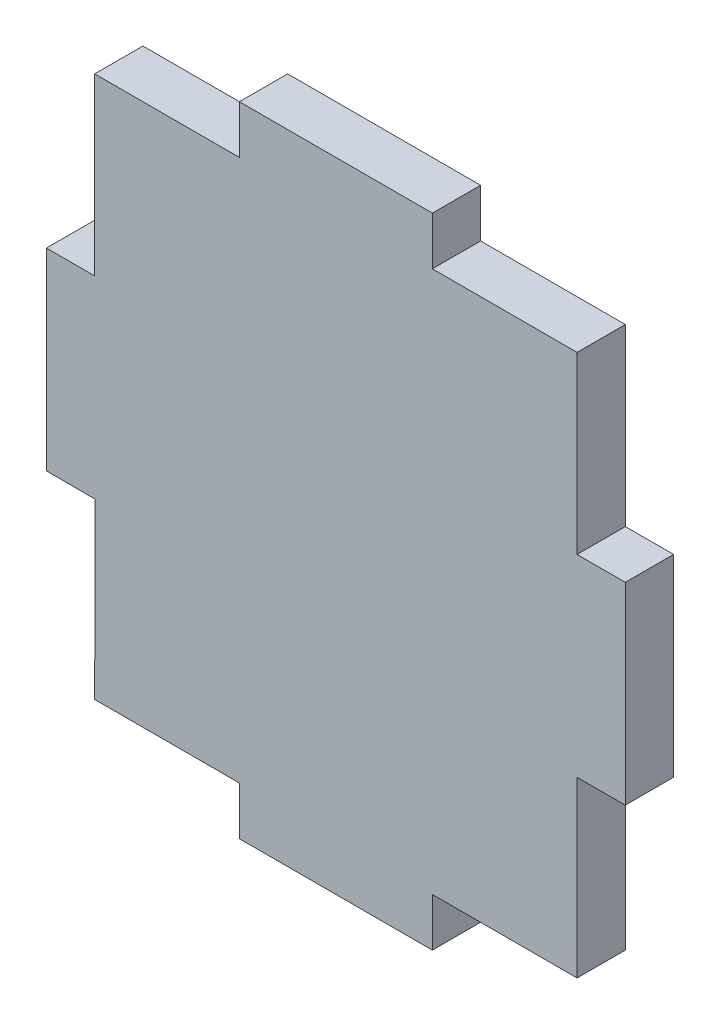
SolidWorks part; units mm, degrees
material "Plain Carbon Steel"
ref_plane "Front Plane" through (0, 0, 0) normal (0, 0, 1) x (1, 0, 0)
ref_plane "Top Plane" through (0, 0, 0) normal (0, 1, 0) x (1, 0, 0)
ref_plane "Right Plane" through (0, 0, 0) normal (1, 0, 0) x (0, 0, -1)
sketch "Model" plane through (0, 0, 0) normal (0, 0, 1) x (1, 0, 0)
  line L0 (823.747, -110.7111) -> (823.747, -92.5742)
  line L1 (838.7355, -148.7291) -> (823.747, -148.7291)
  line L2 (858.747, -148.7291) -> (873.747, -148.7291)
  line L3 (878.747, -130.7111) -> (873.747, -130.7225)
  line L4 (823.747, -92.5742) -> (838.7355, -92.5742)
  line L5 (873.747, -148.7291) -> (873.747, -130.7225)
  line L6 (873.747, -110.7111) -> (878.747, -110.7111)
  line L7 (838.747, -153.7291) -> (858.747, -153.7291)
  line L8 (818.747, -110.7111) -> (823.747, -110.7111)
  line L9 (838.7355, -148.7291) -> (838.747, -153.7291)
  line L10 (838.747, -87.5742) -> (858.747, -87.5742)
  line L11 (838.7355, -92.5742) -> (838.747, -87.5742)
  line L12 (823.7888, -130.7227) -> (818.747, -130.7111)
  line L13 (858.747, -87.5742) -> (858.747, -92.5742)
  line L14 (873.747, -92.5742) -> (873.747, -110.7111)
  line L15 (878.747, -110.7111) -> (878.747, -130.7111)
  line L16 (858.747, -92.5742) -> (873.747, -92.5742)
  line L17 (818.747, -130.7111) -> (818.747, -110.7111)
  line L18 (823.747, -148.7291) -> (823.7888, -130.7227)
  line L19 (858.747, -153.7291) -> (858.747, -148.7291)
  line L20 (841.5508, -121.7141) -> (841.0107, -121.7141)
  line L21 (841.0107, -121.7141) -> (842.0816, -121.7141)
  line L22 (842.0816, -121.7141) -> (841.5508, -121.7141)
  line L23 (841.5508, -121.7141) -> (841.5508, -123.8681)
  line L24 (841.5508, -123.8681) -> (841.5508, -121.7141)
  line L25 (842.5092, -123.8681) -> (842.5092, -121.7141)
  line L26 (842.5092, -121.7141) -> (842.5092, -122.7756)
  line L27 (842.5092, -122.7756) -> (843.6269, -122.7756)
  line L28 (843.6269, -122.7756) -> (843.6269, -121.7141)
  line L29 (843.6269, -121.7141) -> (843.6269, -123.8681)
  line L30 (843.6269, -123.8681) -> (843.6269, -122.7754)
  line L31 (843.6269, -122.7754) -> (842.5092, -122.7754)
  line L32 (842.5092, -122.7754) -> (842.5092, -123.8681)
  line L33 (844.0077, -121.7111) -> (844.0077, -123.8681)
  line L34 (844.5077, -123.4747) -> (844.5077, -123.6277)
  line L35 (844.5077, -123.6277) -> (844.5177, -123.6758)
  line L36 (844.5177, -123.6758) -> (844.5479, -123.7202)
  line L37 (844.5479, -123.7202) -> (844.6685, -123.7978)
  line L38 (844.6685, -123.7978) -> (844.8492, -123.8505)
  line L39 (844.8492, -123.8505) -> (845.0696, -123.8681)
  line L40 (845.0696, -123.8681) -> (845.2901, -123.8505)
  line L41 (845.2901, -123.8505) -> (845.4708, -123.7978)
  line L42 (845.4708, -123.7978) -> (845.5914, -123.7202)
  line L43 (845.5914, -123.7202) -> (845.6216, -123.6758)
  line L44 (845.6216, -123.6758) -> (845.6316, -123.6277)
  line L45 (845.6316, -123.6277) -> (845.6378, -122.9909)
  line L46 (845.6378, -122.9909) -> (845.6096, -122.865)
  line L47 (845.6096, -122.865) -> (845.5282, -122.7747)
  line L48 (845.5282, -122.7747) -> (845.3935, -122.7199)
  line L49 (845.3935, -122.7199) -> (845.2054, -122.7005)
  line L50 (845.2054, -122.7005) -> (844.8648, -122.692)
  line L51 (844.8648, -122.692) -> (844.7012, -122.6725)
  line L52 (844.7012, -122.6725) -> (844.5561, -122.5905)
  line L53 (844.5561, -122.5905) -> (844.5198, -122.5419)
  line L54 (844.5198, -122.5419) -> (844.5077, -122.4883)
  line L55 (844.5077, -122.4883) -> (844.5077, -121.9545)
  line L56 (844.5077, -121.9545) -> (844.5177, -121.9064)
  line L57 (844.5177, -121.9064) -> (844.5479, -121.862)
  line L58 (844.5479, -121.862) -> (844.6685, -121.7843)
  line L59 (844.6685, -121.7843) -> (844.8492, -121.7317)
  line L60 (844.8492, -121.7317) -> (845.0696, -121.7141)
  line L61 (845.0696, -121.7141) -> (845.2901, -121.7317)
  line L62 (845.2901, -121.7317) -> (845.4708, -121.7843)
  line L63 (845.4708, -121.7843) -> (845.5914, -121.862)
  line L64 (845.5914, -121.862) -> (845.6216, -121.9064)
  line L65 (845.6216, -121.9064) -> (845.6316, -121.9545)
  line L66 (845.6316, -121.9545) -> (845.6316, -122.1074)
  line L67 (845.6316, -122.1074) -> (845.6316, -121.9545)
  line L68 (845.6316, -121.9545) -> (845.6216, -121.9064)
  line L69 (845.6216, -121.9064) -> (845.5914, -121.862)
  line L70 (845.5914, -121.862) -> (845.4708, -121.7843)
  line L71 (845.4708, -121.7843) -> (845.2901, -121.7317)
  line L72 (845.2901, -121.7317) -> (845.0696, -121.7141)
  line L73 (845.0696, -121.7141) -> (844.8492, -121.7317)
  line L74 (844.8492, -121.7317) -> (844.6685, -121.7843)
  line L75 (844.6685, -121.7843) -> (844.5479, -121.862)
  line L76 (844.5479, -121.862) -> (844.5177, -121.9064)
  line L77 (844.5177, -121.9064) -> (844.5077, -121.9545)
  line L78 (844.5077, -121.9545) -> (844.5077, -122.4883)
  line L79 (844.5077, -122.4883) -> (844.5198, -122.5419)
  line L80 (844.5198, -122.5419) -> (844.5561, -122.5905)
  line L81 (844.5561, -122.5905) -> (844.7012, -122.6725)
  line L82 (844.7012, -122.6725) -> (844.8648, -122.692)
  line L83 (844.8648, -122.692) -> (845.2054, -122.7005)
  line L84 (845.2054, -122.7005) -> (845.3935, -122.7199)
  line L85 (845.3935, -122.7199) -> (845.5282, -122.7747)
  line L86 (845.5282, -122.7747) -> (845.6096, -122.865)
  line L87 (845.6096, -122.865) -> (845.6378, -122.9909)
  line L88 (845.6378, -122.9909) -> (845.6316, -123.6277)
  line L89 (845.6316, -123.6277) -> (845.6216, -123.6758)
  line L90 (845.6216, -123.6758) -> (845.5914, -123.7202)
  line L91 (845.5914, -123.7202) -> (845.4708, -123.7978)
  line L92 (845.4708, -123.7978) -> (845.2901, -123.8505)
  line L93 (845.2901, -123.8505) -> (845.0696, -123.8681)
  line L94 (845.0696, -123.8681) -> (844.8492, -123.8505)
  line L95 (844.8492, -123.8505) -> (844.6685, -123.7978)
  line L96 (844.6685, -123.7978) -> (844.5479, -123.7202)
  line L97 (844.5479, -123.7202) -> (844.5177, -123.6758)
  line L98 (844.5177, -123.6758) -> (844.5077, -123.6277)
  line L99 (844.5077, -123.6277) -> (844.5077, -123.4747)
  line L100 (847.2516, -123.4747) -> (847.2516, -123.6277)
  line L101 (847.2516, -123.6277) -> (847.2616, -123.6758)
  line L102 (847.2616, -123.6758) -> (847.2918, -123.7202)
  line L103 (847.2918, -123.7202) -> (847.4124, -123.7978)
  line L104 (847.4124, -123.7978) -> (847.5931, -123.8505)
  line L105 (847.5931, -123.8505) -> (847.8135, -123.8681)
  line L106 (847.8135, -123.8681) -> (848.034, -123.8505)
  line L107 (848.034, -123.8505) -> (848.2147, -123.7978)
  line L108 (848.2147, -123.7978) -> (848.3353, -123.7202)
  line L109 (848.3353, -123.7202) -> (848.3655, -123.6758)
  line L110 (848.3655, -123.6758) -> (848.3755, -123.6277)
  line L111 (848.3755, -123.6277) -> (848.3817, -122.9909)
  line L112 (848.3817, -122.9909) -> (848.3535, -122.865)
  line L113 (848.3535, -122.865) -> (848.2721, -122.7747)
  line L114 (848.2721, -122.7747) -> (848.1374, -122.7199)
  line L115 (848.1374, -122.7199) -> (847.9494, -122.7005)
  line L116 (847.9494, -122.7005) -> (847.6087, -122.692)
  line L117 (847.6087, -122.692) -> (847.4451, -122.6725)
  line L118 (847.4451, -122.6725) -> (847.3, -122.5905)
  line L119 (847.3, -122.5905) -> (847.2637, -122.5419)
  line L120 (847.2637, -122.5419) -> (847.2516, -122.4883)
  line L121 (847.2516, -122.4883) -> (847.2516, -121.9545)
  line L122 (847.2516, -121.9545) -> (847.2616, -121.9064)
  line L123 (847.2616, -121.9064) -> (847.2918, -121.862)
  line L124 (847.2918, -121.862) -> (847.4124, -121.7843)
  line L125 (847.4124, -121.7843) -> (847.5931, -121.7317)
  line L126 (847.5931, -121.7317) -> (847.8135, -121.7141)
  line L127 (847.8135, -121.7141) -> (848.034, -121.7317)
  line L128 (848.034, -121.7317) -> (848.2147, -121.7843)
  line L129 (848.2147, -121.7843) -> (848.3353, -121.862)
  line L130 (848.3353, -121.862) -> (848.3655, -121.9064)
  line L131 (848.3655, -121.9064) -> (848.3755, -121.9545)
  line L132 (848.3755, -121.9545) -> (848.3755, -122.1074)
  line L133 (848.3755, -122.1074) -> (848.3755, -121.9545)
  line L134 (848.3755, -121.9545) -> (848.3655, -121.9064)
  line L135 (848.3655, -121.9064) -> (848.3353, -121.862)
  line L136 (848.3353, -121.862) -> (848.2147, -121.7843)
  line L137 (848.2147, -121.7843) -> (848.034, -121.7317)
  line L138 (848.034, -121.7317) -> (847.8135, -121.7141)
  line L139 (847.8135, -121.7141) -> (847.5931, -121.7317)
  line L140 (847.5931, -121.7317) -> (847.4124, -121.7843)
  line L141 (847.4124, -121.7843) -> (847.2918, -121.862)
  line L142 (847.2918, -121.862) -> (847.2616, -121.9064)
  line L143 (847.2616, -121.9064) -> (847.2516, -121.9545)
  line L144 (847.2516, -121.9545) -> (847.2516, -122.4883)
  line L145 (847.2516, -122.4883) -> (847.2637, -122.5419)
  line L146 (847.2637, -122.5419) -> (847.3, -122.5905)
  line L147 (847.3, -122.5905) -> (847.4451, -122.6725)
  line L148 (847.4451, -122.6725) -> (847.6087, -122.692)
  line L149 (847.6087, -122.692) -> (847.9494, -122.7005)
  line L150 (847.9494, -122.7005) -> (848.1374, -122.7199)
  line L151 (848.1374, -122.7199) -> (848.2721, -122.7747)
  line L152 (848.2721, -122.7747) -> (848.3535, -122.865)
  line L153 (848.3535, -122.865) -> (848.3817, -122.9909)
  line L154 (848.3817, -122.9909) -> (848.3755, -123.6277)
  line L155 (848.3755, -123.6277) -> (848.3655, -123.6758)
  line L156 (848.3655, -123.6758) -> (848.3353, -123.7202)
  line L157 (848.3353, -123.7202) -> (848.2147, -123.7978)
  line L158 (848.2147, -123.7978) -> (848.034, -123.8505)
  line L159 (848.034, -123.8505) -> (847.8135, -123.8681)
  line L160 (847.8135, -123.8681) -> (847.5931, -123.8505)
  line L161 (847.5931, -123.8505) -> (847.4124, -123.7978)
  line L162 (847.4124, -123.7978) -> (847.2918, -123.7202)
  line L163 (847.2918, -123.7202) -> (847.2616, -123.6758)
  line L164 (847.2616, -123.6758) -> (847.2516, -123.6277)
  line L165 (847.2516, -123.6277) -> (847.2516, -123.4747)
  line L166 (848.747, -121.7111) -> (848.747, -123.8681)
  line L167 (849.247, -123.8681) -> (849.247, -121.7141)
  line L168 (849.247, -121.7141) -> (849.7559, -121.7141)
  line L169 (849.7559, -121.7141) -> (849.9729, -121.732)
  line L170 (849.9729, -121.732) -> (850.1555, -121.7859)
  line L171 (850.1555, -121.7859) -> (850.2773, -121.8639)
  line L172 (850.2773, -121.8639) -> (850.3077, -121.9076)
  line L173 (850.3077, -121.9076) -> (850.3179, -121.9545)
  line L174 (850.3179, -121.9545) -> (850.3179, -123.6277)
  line L175 (850.3179, -123.6277) -> (850.3077, -123.6759)
  line L176 (850.3077, -123.6759) -> (850.2773, -123.7206)
  line L177 (850.2773, -123.7206) -> (850.1555, -123.7994)
  line L178 (850.1555, -123.7994) -> (849.9776, -123.8509)
  line L179 (849.9776, -123.8509) -> (849.7559, -123.8681)
  line L180 (849.7559, -123.8681) -> (849.247, -123.8681)
  line L181 (849.247, -121.7141) -> (849.247, -123.8681)
  line L182 (849.247, -123.8681) -> (849.7559, -123.8681)
  line L183 (849.7559, -123.8681) -> (849.9776, -123.8509)
  line L184 (849.9776, -123.8509) -> (850.1555, -123.7994)
  line L185 (850.1555, -123.7994) -> (850.2773, -123.7206)
  line L186 (850.2773, -123.7206) -> (850.3077, -123.6759)
  line L187 (850.3077, -123.6759) -> (850.3179, -123.6277)
  line L188 (850.3179, -123.6277) -> (850.3179, -121.9545)
  line L189 (850.3179, -121.9545) -> (850.3077, -121.9076)
  line L190 (850.3077, -121.9076) -> (850.2773, -121.8639)
  line L191 (850.2773, -121.8639) -> (850.1555, -121.7859)
  line L192 (850.1555, -121.7859) -> (849.9729, -121.732)
  line L193 (849.9729, -121.732) -> (849.7559, -121.7141)
  line L194 (849.7559, -121.7141) -> (849.247, -121.7141)
  line L195 (850.7455, -123.8681) -> (850.7455, -121.7141)
  line L196 (850.7455, -121.7141) -> (851.8101, -121.7141)
  line L197 (851.8101, -121.7141) -> (850.7455, -121.7141)
  line L198 (850.7455, -121.7141) -> (850.7455, -122.7599)
  line L199 (850.7455, -122.7599) -> (851.6602, -122.7599)
  line L200 (851.6602, -122.7599) -> (850.7455, -122.7599)
  line L201 (850.7455, -122.7599) -> (850.7455, -123.8681)
  line L202 (850.7455, -123.8681) -> (851.8101, -123.8681)
  line L203 (851.8101, -123.8681) -> (850.7455, -123.8681)
  line L204 (854.6164, -123.6277) -> (854.6063, -123.6758)
  line L205 (854.6063, -123.6758) -> (854.5762, -123.7202)
  line L206 (854.5762, -123.7202) -> (854.4556, -123.7978)
  line L207 (854.4556, -123.7978) -> (854.2749, -123.8505)
  line L208 (854.2749, -123.8505) -> (854.0544, -123.8681)
  line L209 (854.0544, -123.8681) -> (853.8339, -123.8505)
  line L210 (853.8339, -123.8505) -> (853.6532, -123.7978)
  line L211 (853.6532, -123.7978) -> (853.5326, -123.7202)
  line L212 (853.5326, -123.7202) -> (853.5025, -123.6758)
  line L213 (853.5025, -123.6758) -> (853.4925, -123.6277)
  line L214 (853.4925, -123.6277) -> (853.4925, -121.7232)
  line L215 (853.4925, -121.7232) -> (853.4925, -123.6277)
  line L216 (853.4925, -123.6277) -> (853.5025, -123.6758)
  line L217 (853.5025, -123.6758) -> (853.5326, -123.7202)
  line L218 (853.5326, -123.7202) -> (853.6532, -123.7978)
  line L219 (853.6532, -123.7978) -> (853.8339, -123.8505)
  line L220 (853.8339, -123.8505) -> (854.0544, -123.8681)
  line L221 (854.0544, -123.8681) -> (854.2749, -123.8505)
  line L222 (854.2749, -123.8505) -> (854.4556, -123.7978)
  line L223 (854.4556, -123.7978) -> (854.5762, -123.7202)
  line L224 (854.5762, -123.7202) -> (854.6063, -123.6758)
  line L225 (854.6164, -121.7232) -> (854.6164, -123.6277)
  line L226 (855.4998, -122.7599) -> (855.7164, -122.7447)
  line L227 (855.7164, -122.7447) -> (855.8979, -122.6991)
  line L228 (855.8979, -122.6991) -> (856.0208, -122.6285)
  line L229 (856.0208, -122.6285) -> (856.0515, -122.5858)
  line L230 (856.0515, -122.5858) -> (856.0618, -122.5383)
  line L231 (856.0618, -122.5383) -> (856.0618, -121.9545)
  line L232 (856.0618, -121.9545) -> (856.0515, -121.9064)
  line L233 (856.0515, -121.9064) -> (856.0208, -121.862)
  line L234 (856.0208, -121.862) -> (855.8979, -121.7844)
  line L235 (855.8979, -121.7844) -> (855.7164, -121.7317)
  line L236 (855.7164, -121.7317) -> (855.4998, -121.7141)
  line L237 (855.4998, -121.7141) -> (854.9909, -121.7141)
  line L238 (854.9909, -121.7141) -> (854.9909, -122.7599)
  line L239 (854.9909, -122.7599) -> (855.4998, -122.7599)
  line L240 (854.9909, -123.8681) -> (854.9909, -121.7141)
  line L241 (854.9909, -121.7141) -> (855.4998, -121.7141)
  line L242 (855.4998, -121.7141) -> (855.7164, -121.7317)
  line L243 (855.7164, -121.7317) -> (855.8979, -121.7843)
  line L244 (855.8979, -121.7843) -> (856.0208, -121.862)
  line L245 (856.0208, -121.862) -> (856.0515, -121.9064)
  line L246 (856.0515, -121.9064) -> (856.0618, -121.9545)
  line L247 (856.0618, -121.9545) -> (856.0618, -122.5382)
  line L248 (856.0618, -122.5382) -> (856.0515, -122.5857)
  line L249 (856.0515, -122.5857) -> (856.0208, -122.6284)
  line L250 (856.0208, -122.6284) -> (855.8979, -122.699)
  line L251 (855.8979, -122.699) -> (855.7164, -122.7446)
  line L252 (855.7164, -122.7446) -> (855.4998, -122.7599)
  line L253 (855.4998, -122.7599) -> (854.9909, -122.7599)
  line L254 (854.9909, -122.7599) -> (854.9909, -123.8681)
  line L255 (844.4326, -111.3824) -> (843.702, -111.167)
  line L256 (841.2233, -119.4364) -> (841.9444, -119.6424)
  line L257 (845.082, -112.0567) -> (845.0414, -111.8694)
  line L258 (842.8342, -111.0952) -> (841.9569, -111.167)
  line L259 (840.5863, -112.0567) -> (840.5863, -118.7495)
  line L260 (852.6021, -118.9419) -> (852.7227, -119.1195)
  line L261 (856.9077, -111.0952) -> (852.562, -111.0952)
  line L262 (840.7456, -119.1273) -> (841.2233, -119.4364)
  line L263 (851.0387, -111.0952) -> (851.0387, -115.3403)
  line L264 (853.4611, -114.5665) -> (854.8098, -114.3666)
  line L265 (840.6262, -111.8647) -> (840.5863, -112.0567)
  line L266 (852.562, -115.3282) -> (852.999, -114.8193)
  line L267 (852.562, -115.3282) -> (852.562, -111.0952)
  line L268 (856.8968, -114.9582) -> (856.4145, -114.6476)
  line L269 (852.999, -114.8193) -> (853.4611, -114.5665)
  line L270 (845.0414, -111.8694) -> (844.9196, -111.6946)
  line L271 (840.5863, -118.7495) -> (840.6262, -118.947)
  line L272 (844.4326, -119.4364) -> (844.9196, -119.121)
  line L273 (854.8098, -114.3666) -> (855.6917, -114.4369)
  line L274 (843.702, -111.167) -> (842.8342, -111.0952)
  line L275 (855.6917, -114.4369) -> (856.4145, -114.6476)
  line L276 (856.8968, -114.9582) -> (857.0174, -115.1358)
  line L277 (857.0576, -115.3282) -> (857.0576, -118.7495)
  line L278 (857.0174, -115.1358) -> (857.0576, -115.3282)
  line L279 (844.9196, -111.6946) -> (844.4326, -111.3824)
  line L280 (841.9444, -119.6424) -> (842.8342, -119.7111)
  line L281 (845.082, -118.7495) -> (845.082, -118.1377)
  line L282 (846.5681, -115.3403) -> (851.0387, -115.3403)
  line L283 (846.5681, -115.3403) -> (846.5681, -111.0952)
  line L284 (841.2233, -111.3824) -> (840.7456, -111.6883)
  line L285 (845.082, -112.6686) -> (845.082, -112.0567)
  line L286 (846.5681, -119.7111) -> (846.5681, -115.3403)
  line L287 (843.7208, -119.6424) -> (844.4326, -119.4364)
  line L288 (841.9569, -111.167) -> (841.2233, -111.3824)
  line L289 (840.7456, -111.6883) -> (840.6262, -111.8647)
  line L290 (853.9278, -119.6408) -> (853.2051, -119.4301)
  line L291 (845.0414, -118.9423) -> (845.082, -118.7495)
  line L292 (852.7227, -119.1195) -> (853.2051, -119.4301)
  line L293 (844.9196, -119.121) -> (845.0414, -118.9423)
  line L294 (842.8342, -119.7111) -> (843.7208, -119.6424)
  line L295 (852.562, -118.7495) -> (852.6021, -118.9419)
  line L296 (840.6262, -118.947) -> (840.7456, -119.1273)
  line L297 (854.8098, -119.7111) -> (853.9278, -119.6408)
  line L298 (856.8968, -119.1195) -> (856.4145, -119.4301)
  line L299 (855.6917, -119.6408) -> (854.8098, -119.7111)
  line L300 (857.0174, -118.9419) -> (856.8968, -119.1195)
  line L301 (856.4145, -119.4301) -> (855.6917, -119.6408)
  line L302 (851.0387, -115.3403) -> (851.0387, -119.7111)
  line L303 (857.0576, -118.7495) -> (857.0174, -118.9419)
  line L304 (840.5863, -120.7111) -> (856.9077, -120.7111)
  line L305 (830.1701, -122.7277) -> (830.4137, -122.57)
  line L306 (828.5655, -118.7007) -> (828.3266, -118.8537)
  line L307 (832.3618, -118.5571) -> (832.8028, -118.5922)
  line L308 (828.247, -119.0378) -> (828.247, -122.3843)
  line L309 (828.3266, -118.8537) -> (828.2669, -118.9418)
  line L310 (830.4745, -118.9442) -> (830.4137, -118.8568)
  line L311 (829.3709, -118.5571) -> (829.8049, -118.593)
  line L312 (830.4137, -122.57) -> (830.4745, -122.4806)
  line L313 (830.4948, -122.3843) -> (830.4948, -122.0783)
  line L314 (833.4857, -122.3843) -> (833.4656, -122.4804)
  line L315 (829.8049, -118.593) -> (830.1701, -118.7007)
  line L316 (828.247, -122.3843) -> (828.2669, -122.483)
  line L317 (828.5655, -122.7277) -> (828.926, -122.8307)
  line L318 (831.3183, -118.8529) -> (831.5594, -118.6976)
  line L319 (830.4745, -118.9442) -> (830.4948, -119.0378)
  line L320 (831.9208, -118.5922) -> (832.3618, -118.5571)
  line L321 (832.8028, -118.5922) -> (833.1641, -118.6976)
  line L322 (833.4857, -119.3438) -> (833.4857, -119.0378)
  line L323 (829.3709, -118.5571) -> (828.9323, -118.593)
  line L324 (831.9208, -118.5922) -> (831.5594, -118.6976)
  line L325 (831.3183, -118.8529) -> (831.258, -118.9417)
  line L326 (831.258, -118.9417) -> (831.2379, -119.0378)
  line L327 (831.2379, -119.0378) -> (831.2379, -122.3843)
  line L328 (833.4857, -119.0378) -> (833.4656, -118.9417)
  line L329 (830.4948, -119.0378) -> (830.4948, -119.3438)
  line L330 (829.3709, -122.865) -> (829.8143, -122.8307)
  line L331 (828.2669, -118.9418) -> (828.247, -119.0378)
  line L332 (829.8143, -122.8307) -> (830.1701, -122.7277)
  line L333 (830.4745, -122.4806) -> (830.4948, -122.3843)
  line L334 (830.4137, -118.8568) -> (830.1701, -118.7007)
  line L335 (833.4053, -118.8529) -> (833.4656, -118.9417)
  line L336 (828.926, -122.8307) -> (829.3709, -122.865)
  line L337 (828.9323, -118.593) -> (828.5655, -118.7007)
  line L338 (828.2669, -122.483) -> (828.3266, -122.5731)
  line L339 (828.3266, -122.5731) -> (828.5655, -122.7277)
  line L340 (833.4053, -118.8529) -> (833.1641, -118.6976)
  line L341 (833.4053, -122.5692) -> (833.4656, -122.4804)
  line L342 (835.7997, -122.8299) -> (835.3587, -122.865)
  line L343 (836.1611, -122.7245) -> (835.7997, -122.8299)
  line L344 (832.8028, -122.8299) -> (833.1641, -122.7245)
  line L345 (835.3587, -122.865) -> (834.9177, -122.8299)
  line L346 (834.3152, -122.5692) -> (834.5564, -122.7245)
  line L347 (831.3183, -122.5692) -> (831.5594, -122.7245)
  line L348 (831.258, -122.4804) -> (831.3183, -122.5692)
  line L349 (834.4534, -120.4192) -> (834.6844, -120.2927)
  line L350 (835.3587, -120.1928) -> (835.7997, -120.2279)
  line L351 (834.2549, -122.4804) -> (834.3152, -122.5692)
  line L352 (836.1611, -120.3333) -> (836.4023, -120.4886)
  line L353 (833.1641, -122.7245) -> (833.4053, -122.5692)
  line L354 (836.4023, -120.4886) -> (836.4625, -120.5774)
  line L355 (834.2348, -122.3843) -> (834.2549, -122.4804)
  line L356 (836.4826, -122.3843) -> (836.4625, -122.4804)
  line L357 (831.5594, -122.7245) -> (831.9208, -122.8299)
  line L358 (833.4857, -120.7111) -> (833.4857, -122.3843)
  line L359 (836.1611, -122.7245) -> (836.4023, -122.5692)
  line L360 (836.4077, -118.5571) -> (834.2348, -118.5571)
  line L361 (834.6844, -120.2927) -> (835.3587, -120.1928)
  line L362 (836.4625, -122.4804) -> (836.4023, -122.5692)
  line L363 (831.9208, -122.8299) -> (832.3618, -122.865)
  line L364 (836.4826, -122.3843) -> (836.4826, -120.6736)
  line L365 (832.3743, -120.7111) -> (833.4857, -120.7111)
  line L366 (834.2348, -118.5571) -> (834.2348, -120.6736)
  line L367 (836.1611, -120.3333) -> (835.7997, -120.2279)
  line L368 (836.4625, -120.5774) -> (836.4826, -120.6736)
  line L369 (832.3618, -122.865) -> (832.8028, -122.8299)
  line L370 (834.9177, -122.8299) -> (834.5564, -122.7245)
  line L371 (834.2348, -120.6736) -> (834.4534, -120.4192)
  line L372 (831.2379, -122.3843) -> (831.258, -122.4804)
  line L373 (825.747, -120.7111) -> (820.747, -120.7111)
  line L374 (822.747, -119.7111) -> (820.747, -120.7111)
  line L375 (822.747, -121.7111) -> (820.747, -120.7111)
  line L376 (852.5433, -145.5886) -> (852.1819, -145.694)
  line L377 (852.1819, -145.694) -> (851.7409, -145.7291)
  line L378 (847.6201, -143.5502) -> (847.6201, -141.4212)
  line L379 (846.877, -142.2078) -> (846.877, -141.9019)
  line L380 (850.6974, -145.4333) -> (850.6371, -145.3445)
  line L381 (850.9386, -145.5886) -> (850.6974, -145.4333)
  line L382 (847.6201, -145.7291) -> (847.6201, -143.5502)
  line L383 (849.4495, -143.5502) -> (847.6201, -143.5502)
  line L384 (849.7493, -141.4212) -> (847.6201, -141.4212)
  line L385 (850.617, -145.2483) -> (850.6371, -145.3445)
  line L386 (846.8567, -141.8083) -> (846.877, -141.9019)
  line L387 (852.8648, -145.2483) -> (852.8447, -145.3445)
  line L388 (852.8447, -145.3445) -> (852.7844, -145.4333)
  line L389 (852.7844, -145.4333) -> (852.5433, -145.5886)
  line L390 (852.7844, -143.3527) -> (852.8447, -143.4415)
  line L391 (852.8447, -143.4415) -> (852.8648, -143.5377)
  line L392 (852.8648, -143.5377) -> (852.8648, -145.2483)
  line L393 (851.0666, -143.1568) -> (850.8355, -143.2832)
  line L394 (851.7409, -143.0569) -> (852.1819, -143.092)
  line L395 (852.1819, -143.092) -> (852.5433, -143.1974)
  line L396 (852.5433, -143.1974) -> (852.7844, -143.3527)
  line L397 (852.7899, -141.4212) -> (850.617, -141.4212)
  line L398 (850.617, -141.4212) -> (850.617, -143.5377)
  line L399 (850.617, -143.5377) -> (850.8355, -143.2832)
  line L400 (851.7409, -143.0569) -> (851.0666, -143.1568)
  line L401 (851.7409, -145.7291) -> (851.2999, -145.694)
  line L402 (851.2999, -145.694) -> (850.9386, -145.5886)
  line L403 (846.8567, -145.3447) -> (846.7959, -145.4341)
  line L404 (844.9477, -145.5917) -> (844.7088, -145.4372)
  line L405 (844.6491, -145.3471) -> (844.6292, -145.2483)
  line L406 (844.6292, -145.2483) -> (844.6292, -141.9019)
  line L407 (846.877, -144.9424) -> (846.877, -145.2483)
  line L408 (846.1964, -145.6948) -> (845.7531, -145.7291)
  line L409 (845.7531, -145.7291) -> (845.3082, -145.6948)
  line L410 (844.6292, -141.9019) -> (844.6491, -141.8059)
  line L411 (844.6491, -141.8059) -> (844.7088, -141.7177)
  line L412 (844.7088, -141.7177) -> (844.9477, -141.5647)
  line L413 (844.9477, -141.5647) -> (845.3145, -141.4571)
  line L414 (845.7531, -141.4212) -> (846.1871, -141.4571)
  line L415 (846.877, -145.2483) -> (846.8567, -145.3447)
  line L416 (845.3082, -145.6948) -> (844.9477, -145.5917)
  line L417 (844.7088, -145.4372) -> (844.6491, -145.3471)
  line L418 (845.3145, -141.4571) -> (845.7531, -141.4212)
  line L419 (846.7959, -145.4341) -> (846.5523, -145.5917)
  line L420 (846.5523, -145.5917) -> (846.1964, -145.6948)
  line L421 (846.1871, -141.4571) -> (846.5523, -141.5647)
  line L422 (846.5523, -141.5647) -> (846.7959, -141.7208)
  line L423 (846.7959, -141.7208) -> (846.8567, -141.8083)
  line L424 (848.747, -146.7291) -> (848.747, -151.7291)
  line L425 (847.747, -149.7291) -> (848.747, -151.7291)
  line L426 (849.747, -149.7291) -> (848.747, -151.7291)
  line L427 (862.9345, -122.7277) -> (863.178, -122.57)
  line L428 (861.3299, -118.7007) -> (861.091, -118.8537)
  line L429 (865.1262, -118.5571) -> (865.5672, -118.5922)
  line L430 (861.0114, -119.0378) -> (861.0114, -122.3843)
  line L431 (861.091, -118.8537) -> (861.0313, -118.9418)
  line L432 (863.2389, -118.9442) -> (863.178, -118.8568)
  line L433 (862.1353, -118.5571) -> (862.5693, -118.593)
  line L434 (863.178, -122.57) -> (863.2389, -122.4806)
  line L435 (863.2592, -122.3843) -> (863.2592, -122.0783)
  line L436 (866.2501, -122.3843) -> (866.23, -122.4804)
  line L437 (862.5693, -118.593) -> (862.9345, -118.7007)
  line L438 (861.0114, -122.3843) -> (861.0313, -122.483)
  line L439 (861.3299, -122.7277) -> (861.6904, -122.8307)
  line L440 (864.0827, -118.8529) -> (864.3238, -118.6976)
  line L441 (863.2389, -118.9442) -> (863.2592, -119.0378)
  line L442 (864.6852, -118.5922) -> (865.1262, -118.5571)
  line L443 (865.5672, -118.5922) -> (865.9285, -118.6976)
  line L444 (866.2501, -119.3438) -> (866.2501, -119.0378)
  line L445 (862.1353, -118.5571) -> (861.6967, -118.593)
  line L446 (864.6852, -118.5922) -> (864.3238, -118.6976)
  line L447 (864.0827, -118.8529) -> (864.0224, -118.9417)
  line L448 (864.0224, -118.9417) -> (864.0023, -119.0378)
  line L449 (864.0023, -119.0378) -> (864.0023, -122.3843)
  line L450 (866.2501, -119.0378) -> (866.23, -118.9417)
  line L451 (863.2592, -119.0378) -> (863.2592, -119.3438)
  line L452 (862.1353, -122.865) -> (862.5786, -122.8307)
  line L453 (861.0313, -118.9418) -> (861.0114, -119.0378)
  line L454 (862.5786, -122.8307) -> (862.9345, -122.7277)
  line L455 (863.2389, -122.4806) -> (863.2592, -122.3843)
  line L456 (863.178, -118.8568) -> (862.9345, -118.7007)
  line L457 (866.1697, -118.8529) -> (866.23, -118.9417)
  line L458 (861.6904, -122.8307) -> (862.1353, -122.865)
  line L459 (861.6967, -118.593) -> (861.3299, -118.7007)
  line L460 (861.0313, -122.483) -> (861.091, -122.5731)
  line L461 (861.091, -122.5731) -> (861.3299, -122.7277)
  line L462 (866.1697, -118.8529) -> (865.9285, -118.6976)
  line L463 (866.1697, -122.5692) -> (866.23, -122.4804)
  line L464 (868.5641, -122.8299) -> (868.1231, -122.865)
  line L465 (868.9255, -122.7245) -> (868.5641, -122.8299)
  line L466 (865.5672, -122.8299) -> (865.9285, -122.7245)
  line L467 (868.1231, -122.865) -> (867.6821, -122.8299)
  line L468 (867.0796, -122.5692) -> (867.3208, -122.7245)
  line L469 (864.0827, -122.5692) -> (864.3238, -122.7245)
  line L470 (864.0224, -122.4804) -> (864.0827, -122.5692)
  line L471 (867.2177, -120.4192) -> (867.4488, -120.2927)
  line L472 (868.1231, -120.1928) -> (868.5641, -120.2279)
  line L473 (867.0193, -122.4804) -> (867.0796, -122.5692)
  line L474 (868.9255, -120.3333) -> (869.1666, -120.4886)
  line L475 (865.9285, -122.7245) -> (866.1697, -122.5692)
  line L476 (869.1666, -120.4886) -> (869.2269, -120.5774)
  line L477 (866.9992, -122.3843) -> (867.0193, -122.4804)
  line L478 (869.247, -122.3843) -> (869.2269, -122.4804)
  line L479 (864.3238, -122.7245) -> (864.6852, -122.8299)
  line L480 (866.2501, -120.7111) -> (866.2501, -122.3843)
  line L481 (868.9255, -122.7245) -> (869.1666, -122.5692)
  line L482 (869.1721, -118.5571) -> (866.9992, -118.5571)
  line L483 (867.4488, -120.2927) -> (868.1231, -120.1928)
  line L484 (869.2269, -122.4804) -> (869.1666, -122.5692)
  line L485 (864.6852, -122.8299) -> (865.1262, -122.865)
  line L486 (869.247, -122.3843) -> (869.247, -120.6736)
  line L487 (865.1386, -120.7111) -> (866.2501, -120.7111)
  line L488 (866.9992, -118.5571) -> (866.9992, -120.6736)
  line L489 (868.9255, -120.3333) -> (868.5641, -120.2279)
  line L490 (869.2269, -120.5774) -> (869.247, -120.6736)
  line L491 (865.1262, -122.865) -> (865.5672, -122.8299)
  line L492 (867.6821, -122.8299) -> (867.3208, -122.7245)
  line L493 (866.9992, -120.6736) -> (867.2177, -120.4192)
  line L494 (864.0023, -122.3843) -> (864.0224, -122.4804)
  line L495 (871.747, -120.7111) -> (876.747, -120.7111)
  line L496 (874.747, -121.7111) -> (876.747, -120.7111)
  line L497 (874.747, -119.7111) -> (876.747, -120.7111)
  line L498 (852.5433, -99.7416) -> (852.1819, -99.847)
  line L499 (852.1819, -99.847) -> (851.7409, -99.8821)
  line L500 (847.6201, -97.7032) -> (847.6201, -95.5742)
  line L501 (846.877, -96.3608) -> (846.877, -96.0549)
  line L502 (850.6974, -99.5863) -> (850.6371, -99.4975)
  line L503 (850.9386, -99.7416) -> (850.6974, -99.5863)
  line L504 (847.6201, -99.8821) -> (847.6201, -97.7032)
  line L505 (849.4495, -97.7032) -> (847.6201, -97.7032)
  line L506 (849.7493, -95.5742) -> (847.6201, -95.5742)
  line L507 (850.617, -99.4013) -> (850.6371, -99.4975)
  line L508 (846.8567, -95.9613) -> (846.877, -96.0549)
  line L509 (852.8648, -99.4013) -> (852.8447, -99.4975)
  line L510 (852.8447, -99.4975) -> (852.7844, -99.5863)
  line L511 (852.7844, -99.5863) -> (852.5433, -99.7416)
  line L512 (852.7844, -97.5057) -> (852.8447, -97.5945)
  line L513 (852.8447, -97.5945) -> (852.8648, -97.6907)
  line L514 (852.8648, -97.6907) -> (852.8648, -99.4013)
  line L515 (851.0666, -97.3098) -> (850.8355, -97.4362)
  line L516 (851.7409, -97.2099) -> (852.1819, -97.245)
  line L517 (852.1819, -97.245) -> (852.5433, -97.3504)
  line L518 (852.5433, -97.3504) -> (852.7844, -97.5057)
  line L519 (852.7899, -95.5742) -> (850.617, -95.5742)
  line L520 (850.617, -95.5742) -> (850.617, -97.6907)
  line L521 (850.617, -97.6907) -> (850.8355, -97.4362)
  line L522 (851.7409, -97.2099) -> (851.0666, -97.3098)
  line L523 (851.7409, -99.8821) -> (851.2999, -99.847)
  line L524 (851.2999, -99.847) -> (850.9386, -99.7416)
  line L525 (846.8567, -99.4977) -> (846.7959, -99.5871)
  line L526 (844.9477, -99.7447) -> (844.7088, -99.5902)
  line L527 (844.6491, -99.5001) -> (844.6292, -99.4013)
  line L528 (844.6292, -99.4013) -> (844.6292, -96.0549)
  line L529 (846.877, -99.0954) -> (846.877, -99.4013)
  line L530 (846.1964, -99.8478) -> (845.7531, -99.8821)
  line L531 (845.7531, -99.8821) -> (845.3082, -99.8478)
  line L532 (844.6292, -96.0549) -> (844.6491, -95.9589)
  line L533 (844.6491, -95.9589) -> (844.7088, -95.8707)
  line L534 (844.7088, -95.8707) -> (844.9477, -95.7177)
  line L535 (844.9477, -95.7177) -> (845.3145, -95.6101)
  line L536 (845.7531, -95.5742) -> (846.1871, -95.6101)
  line L537 (846.877, -99.4013) -> (846.8567, -99.4977)
  line L538 (845.3082, -99.8478) -> (844.9477, -99.7447)
  line L539 (844.7088, -99.5902) -> (844.6491, -99.5001)
  line L540 (845.3145, -95.6101) -> (845.7531, -95.5742)
  line L541 (846.7959, -99.5871) -> (846.5523, -99.7447)
  line L542 (846.5523, -99.7447) -> (846.1964, -99.8478)
  line L543 (846.1871, -95.6101) -> (846.5523, -95.7177)
  line L544 (846.5523, -95.7177) -> (846.7959, -95.8738)
  line L545 (846.7959, -95.8738) -> (846.8567, -95.9613)
  line L546 (848.747, -94.5742) -> (848.747, -89.5742)
  line L547 (849.747, -91.5742) -> (848.747, -89.5742)
  line L548 (847.747, -91.5742) -> (848.747, -89.5742)
sketch "Sketch2" plane through (0, 0, 0) normal (0, 0, 1) x (1, 0, 0)
  line L0 (838.7355, -92.5742) -> (838.747, -87.5742) construction
  line L1 (823.747, -92.5742) -> (838.7355, -92.5742) construction
  line L2 (823.747, -110.7111) -> (823.747, -92.5742) construction
  line L3 (818.747, -110.7111) -> (823.747, -110.7111) construction
  line L4 (818.747, -130.7111) -> (818.747, -110.7111) construction
  line L5 (823.7888, -130.7227) -> (818.747, -130.7111) construction
  line L6 (823.747, -148.7291) -> (823.7888, -130.7227) construction
  line L7 (838.7355, -148.7291) -> (823.747, -148.7291) construction
  line L8 (838.7355, -148.7291) -> (838.747, -153.7291) construction
  line L9 (838.747, -153.7291) -> (858.747, -153.7291) construction
  line L10 (858.747, -153.7291) -> (858.747, -148.7291) construction
  line L11 (858.747, -148.7291) -> (873.747, -148.7291) construction
  line L12 (873.747, -148.7291) -> (873.747, -130.7225) construction
  line L13 (878.747, -130.7111) -> (873.747, -130.7225) construction
  line L14 (878.747, -110.7111) -> (878.747, -130.7111) construction
  line L15 (873.747, -110.7111) -> (878.747, -110.7111) construction
  line L16 (873.747, -92.5742) -> (873.747, -110.7111) construction
  line L17 (858.747, -92.5742) -> (873.747, -92.5742) construction
  line L18 (858.747, -87.5742) -> (858.747, -92.5742) construction
  line L19 (838.747, -87.5742) -> (858.747, -87.5742) construction
  line L20 (838.7355, -92.5742) -> (838.747, -87.5742)
  line L21 (823.747, -92.5742) -> (838.7355, -92.5742)
  line L22 (823.747, -110.7111) -> (823.747, -92.5742)
  line L23 (818.747, -110.7111) -> (823.747, -110.7111)
  line L24 (818.747, -130.7111) -> (818.747, -110.7111)
  line L25 (823.7888, -130.7227) -> (818.747, -130.7111)
  line L26 (823.747, -148.7291) -> (823.7888, -130.7227)
  line L27 (838.7355, -148.7291) -> (823.747, -148.7291)
  line L28 (838.7355, -148.7291) -> (838.747, -153.7291)
  line L29 (838.747, -153.7291) -> (858.747, -153.7291)
  line L30 (858.747, -153.7291) -> (858.747, -148.7291)
  line L31 (858.747, -148.7291) -> (873.747, -148.7291)
  line L32 (873.747, -148.7291) -> (873.747, -130.7225)
  line L33 (878.747, -130.7111) -> (873.747, -130.7225)
  line L34 (878.747, -110.7111) -> (878.747, -130.7111)
  line L35 (873.747, -110.7111) -> (878.747, -110.7111)
  line L36 (873.747, -92.5742) -> (873.747, -110.7111)
  line L37 (858.747, -92.5742) -> (873.747, -92.5742)
  line L38 (858.747, -87.5742) -> (858.747, -92.5742)
  line L39 (838.747, -87.5742) -> (858.747, -87.5742)
  line L40 (818.747, -120.7111) -> (848.747, -120.7111) construction
  line L41 (848.747, -87.5742) -> (848.747, -120.7111) construction
extrude "Boss-Extrude1" add sketch "Sketch2" along normal mid plane 5
ref_plane "Plane1" through (0, -120.7111, 0) normal (0, 1, 0) x (1, 0, 0)
ref_plane "Plane2" through (848.747, 0, 0) normal (1, 0, 0) x (0, 0, -1)
